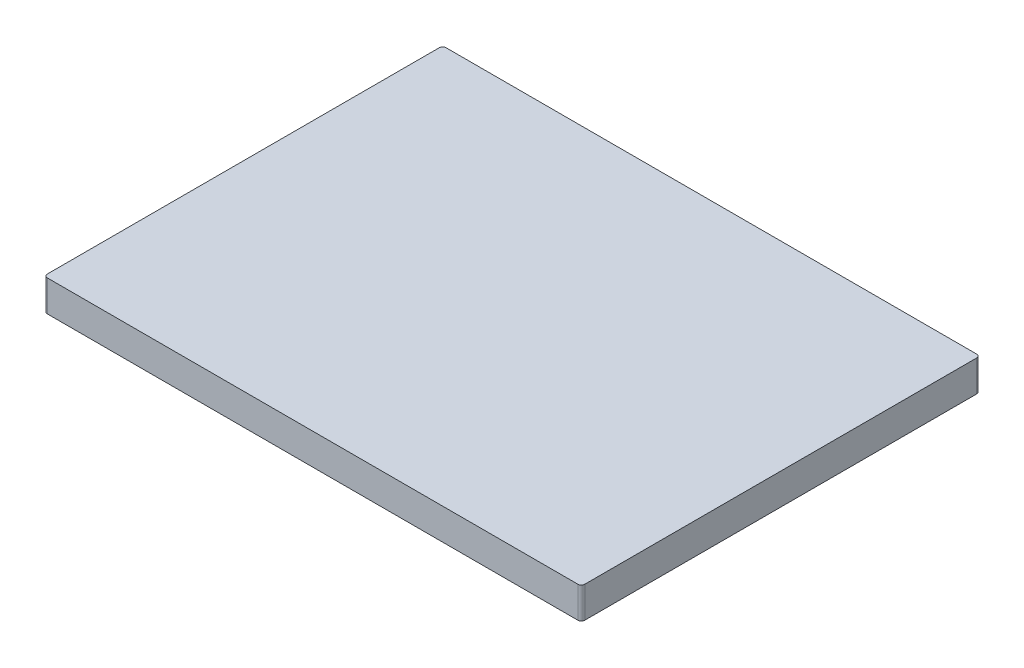
SolidWorks part; units mm, degrees
ref_plane "Front Plane" through (0, 0, 0) normal (0, 0, 1) x (1, 0, 0)
ref_plane "Top Plane" through (0, 0, 0) normal (0, 1, 0) x (1, 0, 0)
ref_plane "Right Plane" through (0, 0, 0) normal (1, 0, 0) x (0, 0, -1)
sketch "Sketch1" plane through (0, 0, 0) normal (0, 1, 0) x (1, 0, 0)
  line L1 (-71.5, 50.5) -> (71.5, 50.5)
  line L2 (-71.5, 50.5) -> (-71.5, -50.5)
  line L3 (-71.5, -50.5) -> (71.5, -50.5)
  line L4 (71.5, 50.5) -> (71.5, -50.5)
  line L5 (-71.5, 50.5) -> (71.5, -50.5) construction
  line L6 (-71.5, -50.5) -> (71.5, 50.5) construction
  point P0 (0, 0)
  dimension "D1" = 101
  dimension "D2" = 143
extrude "Boss-Extrude1" add sketch "Sketch1" along normal blind 4
sketch "Sketch2" plane through (0, 4, 0) normal (0, 1, 0) x (1, 0, 0)
  line L1 (77.5, 57.5) -> (-77.5, 57.5)
  line L2 (77.5, 57.5) -> (77.5, -57.5)
  line L3 (77.5, -57.5) -> (-77.5, -57.5)
  line L4 (-77.5, 57.5) -> (-77.5, -57.5)
  line L5 (77.5, 57.5) -> (-77.5, -57.5) construction
  line L6 (77.5, -57.5) -> (-77.5, 57.5) construction
  point P0 (0, 0)
  dimension "D1" = 155
  dimension "D2" = 115
extrude "Boss-Extrude2" add sketch "Sketch2" along normal blind 4
fillet "Fillet1" radius 5 4 edges at (71.5, 2, 50.5) (71.5, 2, -50.5) (-71.5, 2, -50.5) (-71.5, 2, 50.5)
fillet "Fillet2" radius 1 4 edges at (-77.5, 6, 57.5) (-77.5, 6, -57.5) (77.5, 6, -57.5) (77.5, 6, 57.5)
sketch "Sketch3" plane through (0, 4, 0) normal (0, -1, 0) x (-1, 0, 0)
  line L0 (-75, -55) -> (75, -55)
  line L1 (75, -55) -> (75, 55)
  line L2 (75, 55) -> (-75, 55)
  line L3 (-75, 55) -> (-75, -55)
  line L12 (-76.5, -57.5) -> (76.5, -57.5)
  line L13 (77.5, -56.5) -> (77.5, 56.5)
  line L14 (76.5, 57.5) -> (-76.5, 57.5)
  line L15 (-77.5, 56.5) -> (-77.5, -56.5)
  line L16 (-76.5, -57.5) -> (76.5, -57.5)
  line L17 (77.5, -56.5) -> (77.5, 56.5)
  line L18 (76.5, 57.5) -> (-76.5, 57.5)
  line L19 (-77.5, 56.5) -> (-77.5, -56.5)
  arc A1 (75, -55) -> (75, -55) centre (75, -55) ccw
  arc A2 (75, 55) -> (75, 55) centre (75, 55) ccw
  arc A3 (-75, 55) -> (-75, 55) centre (-75, 55) ccw
  arc A4 (-75, -55) -> (-75, -55) centre (-75, -55) ccw
  arc A12 (76.5, -57.5) -> (77.5, -56.5) centre (76.5, -56.5) ccw
  arc A13 (77.5, 56.5) -> (76.5, 57.5) centre (76.5, 56.5) ccw
  arc A14 (-76.5, 57.5) -> (-77.5, 56.5) centre (-76.5, 56.5) ccw
  arc A15 (-77.5, -56.5) -> (-76.5, -57.5) centre (-76.5, -56.5) ccw
  arc A16 (76.5, -57.5) -> (77.5, -56.5) centre (76.5, -56.5) ccw
  arc A17 (77.5, 56.5) -> (76.5, 57.5) centre (76.5, 56.5) ccw
  arc A18 (-76.5, 57.5) -> (-77.5, 56.5) centre (-76.5, 56.5) ccw
  arc A19 (-77.5, -56.5) -> (-76.5, -57.5) centre (-76.5, -56.5) ccw
  dimension "D1" = 0
  dimension "D2" = 2.5
extrude "Boss-Extrude3" add sketch "Sketch3" along normal blind 5
